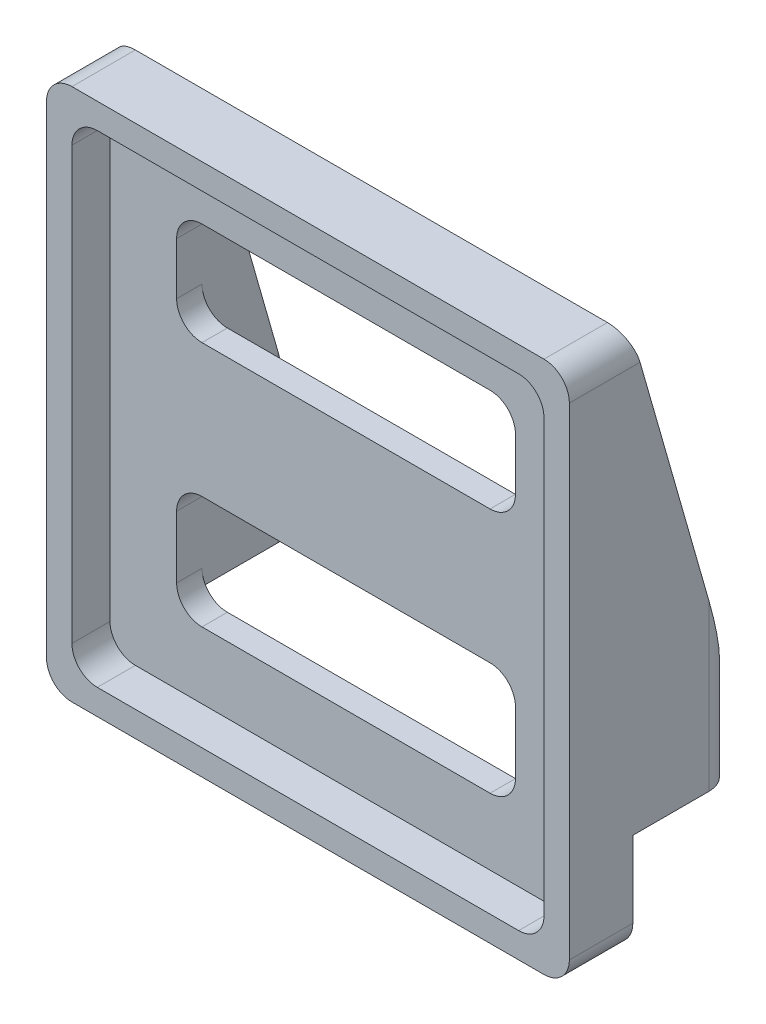
SolidWorks part; units mm, degrees
ref_plane "Front Plane" through (0, 0, 0) normal (0, 0, 1) x (1, 0, 0)
ref_plane "Top Plane" through (0, 0, 0) normal (0, 1, 0) x (1, 0, 0)
ref_plane "Right Plane" through (0, 0, 0) normal (1, 0, 0) x (0, 0, -1)
sketch "Sketch1" plane through (0, 0, 0) normal (0, 0, 1) x (1, 0, 0)
  line L1 (0, 0) -> (41.2, 0)
  line L2 (0, 0) -> (0, -42)
  line L3 (0, -42) -> (41.2, -42)
  line L4 (41.2, 0) -> (41.2, -42)
  dimension "D1" = 41.2
  dimension "D2" = 42
extrude "Boss-Extrude1" add sketch "Sketch1" along normal blind 5 contours L1 L4 L3 L2
sketch "Sketch2" plane through (0, 0, 5) normal (0, 0, 1) x (1, 0, 0)
  line L0 (0, 0) -> (41.2, 0) construction
  line L1 (4, -2) -> (37.2, -2)
  line L2 (2, -4) -> (2, -38)
  line L3 (4, -40) -> (37.2, -40)
  line L4 (39.2, -4) -> (39.2, -38)
  line L5 (0, -42) -> (41.2, -42) construction
  line L6 (0, 0) -> (0, -42) construction
  line L7 (41.2, 0) -> (41.2, -42) construction
  arc A0 (37.2, -2) -> (39.2, -4) centre (37.2, -4) cw
  arc A1 (37.2, -40) -> (39.2, -38) centre (37.2, -38) ccw
  arc A2 (2, -38) -> (4, -40) centre (4, -38) ccw
  arc A3 (4, -2) -> (2, -4) centre (4, -4) ccw
  dimension "D5" = 2
  dimension "D1" = 2
  dimension "D2" = 2
  dimension "D3" = 2
  dimension "D4" = 2
extrude "Cut-Extrude1" cut sketch "Sketch2" against normal blind 3
sketch "Sketch3" plane through (0, 0, 2) normal (0, 0, 1) x (1, 0, 0)
  line L0 (37.2, -2) -> (4, -2) construction
  line L1 (9.25, -7.25) -> (31.95, -7.25)
  line L2 (7.25, -9.25) -> (7.25, -13.35)
  line L3 (9.25, -15.35) -> (31.95, -15.35)
  line L4 (33.95, -9.25) -> (33.95, -13.35)
  line L5 (9.25, -25.85) -> (31.95, -25.85)
  line L6 (7.25, -27.85) -> (7.25, -32.75)
  line L7 (9.25, -34.75) -> (31.95, -34.75)
  line L8 (33.95, -27.85) -> (33.95, -32.75)
  line L9 (4, -40) -> (37.2, -40) construction
  line L10 (2, -4) -> (2, -38) construction
  line L11 (39.2, -38) -> (39.2, -4) construction
  arc A0 (31.95, -34.75) -> (33.95, -32.75) centre (31.95, -32.75) ccw
  arc A1 (7.25, -32.75) -> (9.25, -34.75) centre (9.25, -32.75) ccw
  arc A2 (9.25, -25.85) -> (7.25, -27.85) centre (9.25, -27.85) ccw
  arc A3 (31.95, -25.85) -> (33.95, -27.85) centre (31.95, -27.85) cw
  arc A4 (31.95, -7.25) -> (33.95, -9.25) centre (31.95, -9.25) cw
  arc A5 (31.95, -15.35) -> (33.95, -13.35) centre (31.95, -13.35) ccw
  arc A6 (7.25, -13.35) -> (9.25, -15.35) centre (9.25, -13.35) ccw
  arc A7 (9.25, -7.25) -> (7.25, -9.25) centre (9.25, -9.25) ccw
  dimension "D9" = 2
  dimension "D1" = 5.25
  dimension "D2" = 5.25
  dimension "D3" = 5.25
  dimension "D4" = 5.25
  dimension "D5" = 5.25
  dimension "D6" = 5.25
  dimension "D7" = 10.5
  dimension "D8" = 8.1
extrude "Cut-Extrude2" cut sketch "Sketch3" against normal up to surface (2 mm away) up to face at (20.6, -21, 0)
ref_plane "Plane1" through (0, -34, 0) normal (0, -1, 0) x (-1, 0, 0)
sketch "Sketch8" plane through (0, 0, 0) normal (0, 0, -1) x (-1, 0, 0)
  line L0 (-33.95, -27.85) -> (-33.95, -32.75) construction
  line L1 (-41.2, -28) -> (-33.95, -28)
  line L2 (-41.2, -28) -> (-41.2, -34)
  line L3 (-41.2, -34) -> (-33.95, -34)
  line L4 (-33.95, -28) -> (-33.95, -34)
  line L5 (-12.2851, -34) -> (12.2851, -34) construction
  line L6 (-41.2, 0) -> (-41.2, -42) construction
  dimension "D1" = 6
sketch "Sketch9" plane through (0, 0, 0) normal (0, 0, -1) x (-1, 0, 0)
  line L0 (-7.25, -32.75) -> (-7.25, -27.85) construction
  line L1 (0, -28) -> (-7.25, -28)
  line L2 (0, -28) -> (0, -34)
  line L3 (0, -34) -> (-7.25, -34)
  line L4 (-7.25, -28) -> (-7.25, -34)
  line L5 (-12.2851, -34) -> (12.2851, -34) construction
  line L6 (0, 0) -> (0, -42) construction
  dimension "D1" = 6
extrude "Boss-Extrude4" add sketch "Sketch8" along normal blind 8
extrude "Boss-Extrude5" add sketch "Sketch9" along normal blind 8
ref_plane "Plane2" through (20.6, 0, 0) normal (1, 0, 0) x (0, 0, -1)
sketch "Sketch12" plane through (0, -28, 0) normal (0, 1, 0) x (1, 0, 0)
  line L0 (37.575, 0) -> (37.575, 8) construction
  line L1 (33.95, 0) -> (41.2, 0) construction
  line L2 (33.95, 8) -> (41.2, 8) construction
  line L3 (41.2, 4) -> (33.95, 4) construction
  line L4 (41.2, 8) -> (41.2, 0) construction
  line L5 (33.95, 8) -> (33.95, 0) construction
  circle A0 centre (37.575, 4) radius 2
  dimension "D1" = 4
extrude "Cut-Extrude4" cut sketch "Sketch12" against normal blind 6
sketch "Sketch13" plane through (41.2, 0, 0) normal (1, 0, 0) x (0, 0, -1)
  line L0 (8, -28) -> (0, 0)
  line L1 (0, 0) -> (0, -28)
  line L2 (0, -28) -> (8, -28)
extrude "Boss-Extrude6" add sketch "Sketch13" against normal blind 7.25
mirror "Mirror2" about plane through (20.6, 0, 0) normal (1, 0, 0) of "Cut-Extrude4", "Boss-Extrude6"
fillet "Fillet1" radius 2 4 edges at (41.2, -42, 2.5) (0, -42, 2.5) (0, 0, 2.5) (41.2, 0, 2.5)
fillet "Fillet2" radius 2 4 edges at (0, -31, -8) (7.25, -31, -8) (33.95, -31, -8) (41.2, -31, -8)
